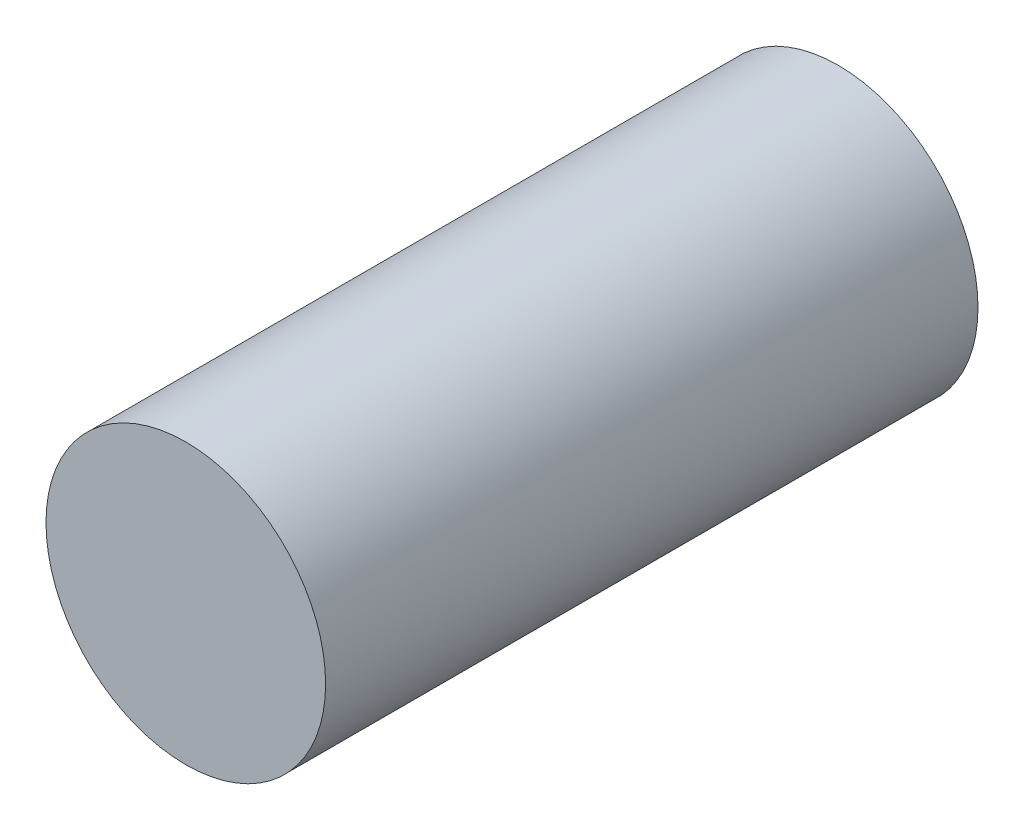
SolidWorks part; units mm, degrees
ref_plane "Plan de face" through (0, 0, 0) normal (0, 0, 1) x (1, 0, 0)
ref_plane "Plan de dessus" through (0, 0, 0) normal (0, 1, 0) x (1, 0, 0)
ref_plane "Plan de droite" through (0, 0, 0) normal (1, 0, 0) x (0, 0, -1)
sketch "Esquisse1" plane through (0, 0, 0) normal (0, 0, 1) x (1, 0, 0)
  circle A0 centre (0, 0) radius 15
  dimension "D1" = 30
extrude "Boss.-Extru.1" add sketch "Esquisse1" along normal blind 70
